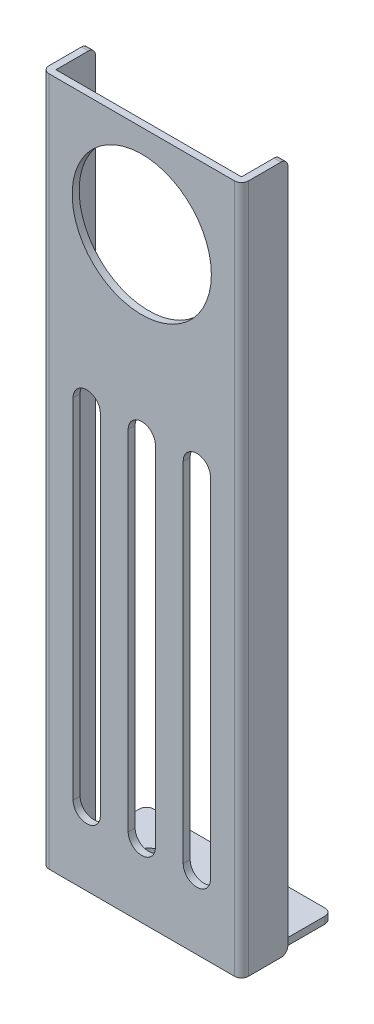
SolidWorks part; units mm, degrees
material "6063-T5"
ref_plane "Alzado" through (0, 0, 0) normal (0, 0, 1) x (1, 0, 0)
ref_plane "Planta" through (0, 0, 0) normal (0, 1, 0) x (1, 0, 0)
ref_plane "Vista lateral" through (0, 0, 0) normal (1, 0, 0) x (0, 0, -1)
sketch "Croquis1" plane through (0, 0, 0) normal (0, 0, 1) x (1, 0, 0)
  line L1 (-52.3033, -28.4523) -> (-12.3033, -28.4523)
  line L2 (-12.3033, -28.4523) -> (-12.3033, 120.0477)
  line L3 (-12.3033, 120.0477) -> (-52.3033, 120.0477)
  line L5 (-52.3033, 120.0477) -> (-52.3033, -28.4523)
  dimension "D1" = 148.5
  dimension "D2" = 40
extrude "Saliente-Extruir1" add sketch "Croquis1" along normal blind 1.5
sketch "Croquis2" plane through (0, 0, 1.5) normal (0, 0, 1) x (1, 0, 0)
  line L0 (-12.3033, 120.0477) -> (-52.3033, 120.0477) construction
  line L5 (-52.3033, 120.0477) -> (-52.3033, -28.4523) construction
  circle A0 centre (-32.3033, 100.0477) radius 15
  dimension "D3" = 30
  dimension "D1" = 20
  dimension "D2" = 20
extrude "Cortar-Extruir1" cut sketch "Croquis2" against normal blind 1.5 contours A0
sketch "Croquis3" plane through (0, 0, 1.5) normal (0, 0, 1) x (1, 0, 0)
  line L0 (-52.3033, -12.9523) -> (-47.1033, -12.9523)
  line L1 (-52.3033, 120.0477) -> (-52.3033, -28.4523) construction
  line L2 (-52.3033, -28.4523) -> (-12.3033, -28.4523) construction
  line L4 (-17.5033, -12.9523) -> (-12.3033, -12.9523)
  line L5 (-12.3033, -28.4523) -> (-12.3033, 120.0477) construction
  line L6 (-23.37, -12.9523) -> (-29.37, -12.9523)
  line L7 (-41.2366, -12.9523) -> (-35.2366, -12.9523)
  line L9 (-47.1033, 62.1777) -> (-47.1033, -12.9523)
  line L10 (-41.2366, -12.9523) -> (-41.2366, 62.1777)
  line L11 (-29.37, -12.9523) -> (-29.37, 62.1777)
  line L12 (-35.2366, 62.1777) -> (-35.2366, -12.9523)
  line L13 (-23.37, 62.1777) -> (-23.37, -12.9523)
  line L14 (-17.5033, 62.1777) -> (-17.5033, -12.9523)
  arc A0 (-47.1033, -12.9523) -> (-41.2366, -12.9523) centre (-44.17, -12.9523) ccw
  arc A1 (-35.2366, -12.9523) -> (-29.37, -12.9523) centre (-32.3033, -12.9523) ccw
  arc A2 (-23.37, -12.9523) -> (-17.5033, -12.9523) centre (-20.4366, -12.9523) ccw
  arc A3 (-41.2366, 62.1777) -> (-47.1033, 62.1777) centre (-44.17, 62.1777) ccw
  arc A4 (-29.37, 62.1777) -> (-35.2366, 62.1777) centre (-32.3033, 62.1777) ccw
  arc A5 (-17.5033, 62.1777) -> (-23.37, 62.1777) centre (-20.4366, 62.1777) ccw
  dimension "D5" = 75.13
  dimension "D6" = 5.8667
  dimension "D1" = 5.2
  dimension "D2" = 5.2
  dimension "D3" = 6
  dimension "D4" = 6
  dimension "D7" = 15.5
extrude "Cortar-Extruir2" cut sketch "Croquis3" against normal blind 1.5 contours L10 A3 L9 A0 | L11 A4 L12 A1 | L14 A5 L13 A2
sketch "Croquis4" plane through (-52.3033, 0, 0) normal (-1, 0, 0) x (0, 0, 1)
  line L0 (1.5, 120.0477) -> (-8.5, 120.0477)
  line L1 (-8.5, 120.0477) -> (-8.5, -28.4523)
  line L2 (-8.5, -28.4523) -> (1.5, -28.4523)
  line L3 (1.5, -28.4523) -> (1.5, 120.0477)
  dimension "D1" = 10
extrude "Saliente-Extruir2" add sketch "Croquis4" along normal blind 1.5 contours L3 L0 L1 L2
sketch "Croquis5" plane through (-12.3033, 0, 0) normal (1, 0, 0) x (0, 0, -1)
  line L0 (-1.5, 120.0477) -> (8.5, 120.0477)
  line L1 (8.5, 120.0477) -> (8.5, -28.4523)
  line L2 (8.5, -28.4523) -> (-1.5, -28.4523)
  line L3 (-1.5, -28.4523) -> (-1.5, 120.0477)
  dimension "D1" = 10
extrude "Saliente-Extruir3" add sketch "Croquis5" along normal blind 1.5
fillet "Redondeo1" radius 1.5 2 edges at (-53.8033, 45.7977, 1.5) (-10.8033, 45.7977, 1.5)
sketch "Croquis7" plane through (0, -28.4523, 0) normal (0, -1, 0) x (1, 0, 0)
  line L0 (-52.3033, -19.5) -> (-52.3033, 1.5)
  line L1 (-52.3033, 1.5) -> (-12.3033, 1.5)
  line L2 (-12.3033, 1.5) -> (-12.3033, -19.5)
  line L3 (-12.3033, -19.5) -> (-52.3033, -19.5)
  dimension "D1" = 21
extrude "Saliente-Extruir4" add sketch "Croquis7" against normal blind 1.5 contours L0 L1 L2 L3
fillet "Redondeo2" radius 1.5 1 edges at (-32.3033, -26.9523, 0)
sketch "Croquis8" plane through (0, -28.4523, 0) normal (0, -1, 0) x (-1, 0, 0)
  line L2 (52.3033, 19.5) -> (52.3033, 8.5) construction
  line L3 (12.3033, 8.5) -> (12.3033, 19.5) construction
  line L5 (12.3033, 19.5) -> (52.3033, 19.5) construction
  circle A0 centre (42.0533, 9.75) radius 2.75
  circle A1 centre (22.5533, 9.75) radius 2.75
  dimension "D3" = 5.5
  dimension "D4" = 9.75
  dimension "D5" = 9.75
  dimension "D1" = 10.25
  dimension "D2" = 10.25
extrude "Cortar-Extruir3" cut sketch "Croquis8" against normal blind 1.5
fillet "Redondeo4" radius 1.5 6 edges at (-53.0533, 120.0477, -8.5) (-11.5533, 120.0477, -8.5) (-53.0533, -28.4523, -8.5) (-52.3033, -27.7023, -19.5) (-12.3033, -27.7023, -19.5) (-11.5533, -28.4523, -8.5)
sketch "Croquis9" plane through (0, -26.9523, 0) normal (0, 1, 0) x (1, 0, 0)
  line L2 (4.3537, 9.75) -> (-59.9058, 9.75) construction
ref_plane "Plano1" through (0, -28.4523, 0) normal (0, -1, 0) x (-1, 0, 0)
sketch "Croquis10" plane through (0, -28.4523, 0) normal (0, -1, 0) x (-1, 0, 0)
  line L0 (-4.3537, 9.75) -> (59.9058, 9.75) construction
equation "\"ç\"=1.5"
